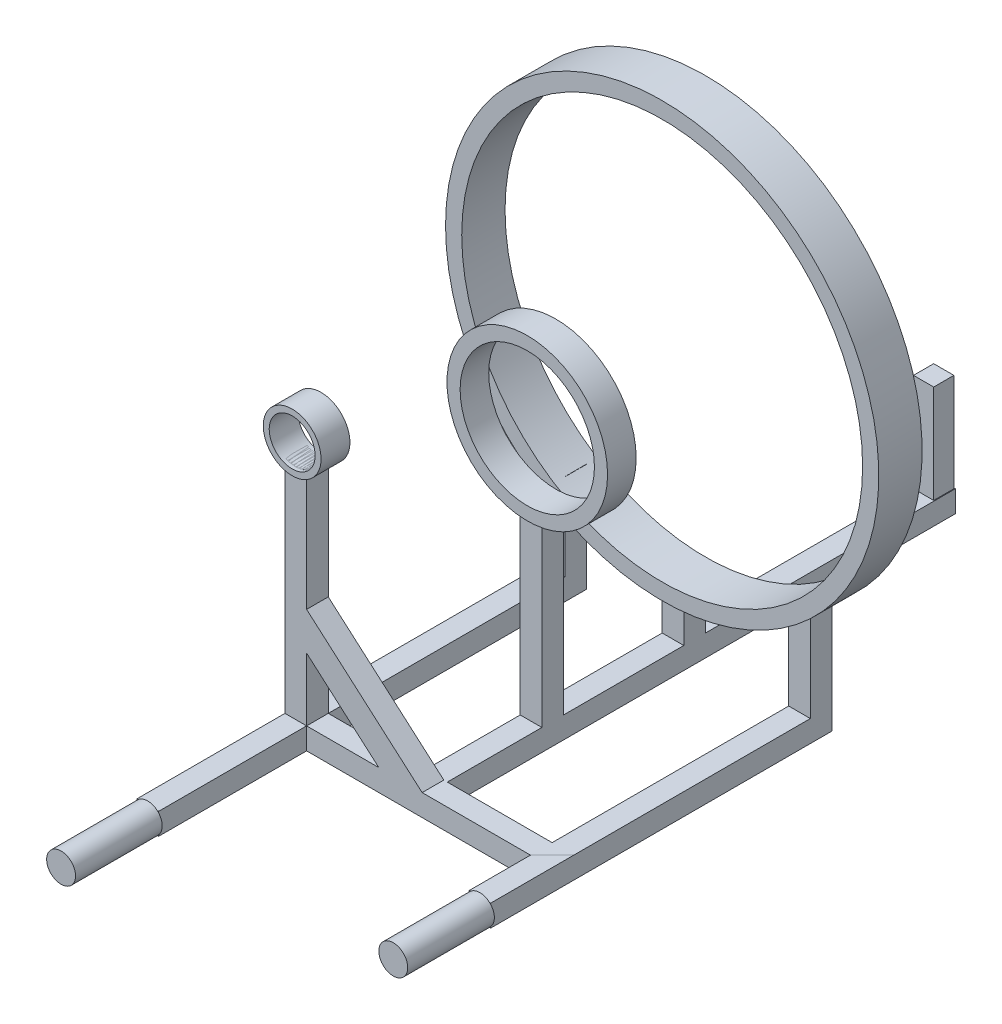
SolidWorks part; units mm, degrees
other "Markup1"
sketch "Sketch15" plane through (18.05, 14, 0) normal (0.0458, 0.1049, 0.9934) x (0.9989, -0.0157, -0.0444)
ref_plane "Front Plane" through (0, 0, 0) normal (0, 0, 1) x (1, 0, 0)
ref_plane "Top Plane" through (0, 0, 0) normal (0, 1, 0) x (1, 0, 0)
ref_plane "Right Plane" through (0, 0, 0) normal (1, 0, 0) x (0, 0, -1)
sketch "Sketch3" plane through (0, 0, 0) normal (0, 0, 1) x (1, 0, 0)
  line L1 (-0.7503, 0.75) -> (0.7497, 0.75)
  line L2 (-0.7503, 0.75) -> (-0.7503, -0.75)
  line L3 (-0.7503, -0.75) -> (0.7497, -0.75)
  line L4 (0.7497, 0.75) -> (0.7497, -0.75)
  line L5 (-0.7503, 0.75) -> (0.7497, -0.75) construction
  line L6 (-0.7503, -0.75) -> (0.7497, 0.75) construction
  dimension "D1" = 1.5
  dimension "D2" = 1.5
sketch "Sketch4" plane through (0, 0, 0) normal (0, 1, 0) x (1, 0, 0)
  line L0 (0, 0) -> (0, 11)
  line L1 (0, 11) -> (17, 11)
  line L2 (17, 11) -> (17, 6)
  dimension "D1" = 17
  dimension "D2" = 11
  dimension "D3" = 5
sweep "Sweep3" add profiles "Sketch3" path "Sketch4"
sketch "Sketch7" plane through (0, 0, 0) normal (0, 1, 0) x (1, 0, 0)
  line L0 (-0.7503, 0) -> (-0.7503, 11.7503) construction
  line L2 (-0.7297, 11.7497) -> (0.7497, 11.7497)
  line L3 (-0.7297, 11.7497) -> (-0.7297, 10.2503)
  line L4 (-0.7297, 10.2503) -> (0.7497, 10.2503)
  line L5 (0.7497, 11.7497) -> (0.7497, 10.2503)
  line L6 (-0.7297, 11.7497) -> (0.7497, 10.2503) construction
  line L7 (-0.7297, 10.2503) -> (0.7497, 11.7497) construction
  circle A0 centre (0.01, 11) radius 0.5 construction
  dimension "D1" = 1
  dimension "D2" = 0.7603
  dimension "D5" = 11
extrude "Boss-Extrude1" add sketch "Sketch7" along normal blind 19
ref_plane "Plane8" through (0, 0, -11) normal (0, 0, 1) x (1, 0, 0)
sketch "Sketch12" plane through (0, 0, -11) normal (0, 0, 1) x (1, 0, 0)
  circle A1 centre (0, 17.5) radius 2
  dimension "D1" = 0
  dimension "D2" = 4
  dimension "D3" = 17.5
extrude "Boss-Extrude4" add sketch "Sketch12" along normal mid plane 2 separate body
ref_plane "Plane9" through (9.09, 0, 0) normal (1, 0, 0) x (0, 0, -1)
sketch "Sketch16" plane through (0, 0, -12) normal (0, 0, -1) x (-1, 0, 0)
  circle A0 centre (0, 17.5) radius 1.59
extrude "Cut-Extrude1" cut sketch "Sketch16" against normal blind 10
sketch "Sketch17" plane through (0, 0, 0) normal (0, 0, 1) x (1, 0, 0)
  circle A0 centre (0, 0) radius 1
  dimension "D1" = 2
extrude "Boss-Extrude5" add sketch "Sketch17" along normal blind 6
sketch "Sketch18" plane through (0, 0, -6) normal (0, 0, 1) x (1, 0, 0)
  line L0 (17.7503, 0.75) -> (17.7503, -0.75) construction
  line L1 (16.2503, 0.75) -> (17.7503, 0.75) construction
  circle A0 centre (17.0006, 0) radius 1
  dimension "D1" = 2
  dimension "D2" = 0.7497
  dimension "D3" = 0.75
extrude "Boss-Extrude6" add sketch "Sketch18" along normal blind 6
ref_plane "Plane10" through (0, 0, -11.75) normal (0, 0, 1) x (1, 0, 0)
sketch "Sketch19" plane through (0, 0, -11.75) normal (0, 0, 1) x (1, 0, 0)
  line L0 (0.7497, -0.75) -> (16.2503, -0.75) construction
  line L1 (7.49, 0.75) -> (8.99, 0.75)
  line L2 (7.49, 0.75) -> (7.49, -0.75)
  line L3 (7.49, -0.75) -> (8.99, -0.75)
  line L4 (8.99, 0.75) -> (8.99, -0.75)
  line L5 (7.49, 0.75) -> (8.99, -0.75) construction
  line L6 (7.49, -0.75) -> (8.99, 0.75) construction
  point P0 (8.24, 0)
  dimension "D1" = 1.5
  dimension "D2" = 1.5
  dimension "D3" = 8.24
extrude "Boss-Extrude7" add sketch "Sketch19" against normal blind 8.05 separate body
sketch "Sketch21" plane through (0, 0.75, 0) normal (0, 1, 0) x (1, 0, 0)
  line L0 (8.99, 19.8) -> (8.99, 11.75) construction
  line L1 (7.49, 19.8) -> (8.99, 19.8)
  line L2 (7.49, 19.8) -> (7.49, 18.3)
  line L3 (7.49, 18.3) -> (8.99, 18.3)
  line L4 (8.99, 19.8) -> (8.99, 18.3)
  dimension "D2" = 1.5
extrude "Boss-Extrude8" add sketch "Sketch21" along normal blind 17.68
ref_plane "Plane11" through (0, 0, -19.05) normal (0, 0, 1) x (1, 0, 0)
sketch "Sketch22" plane through (0, 0, -19.05) normal (0, 0, 1) x (1, 0, 0)
  line L0 (7.49, 0.75) -> (8.99, 0.75) construction
  circle A0 centre (8.2196, 18.43) radius 5.56
  point P4 (8.24, 0.75)
  dimension "D1" = 11.12
  dimension "D2" = 17.68
extrude "Boss-Extrude9" add sketch "Sketch22" along normal mid plane 1.98
sketch "Sketch23" plane through (0, 0, -20.04) normal (0, 0, -1) x (-1, 0, 0)
  circle A0 centre (-8.2196, 18.43) radius 4.65
extrude "Cut-Extrude2" cut sketch "Sketch23" against normal blind 5
sketch "Sketch24" plane through (0, 0, -19.8) normal (0, 0, -1) x (-1, 0, 0)
  line L0 (-7.49, 0.75) -> (-8.99, 0.75) construction
  line L1 (-8.99, -0.75) -> (-7.49, -0.75)
  line L2 (-8.99, -0.75) -> (-8.99, 0.75)
  line L3 (-8.99, 0.75) -> (-7.49, 0.75)
  line L4 (-7.49, -0.75) -> (-7.49, 0.75)
  line L5 (-7.49, 0.75) -> (-8.99, 0.75) construction
extrude "Boss-Extrude10" add sketch "Sketch24" along normal blind 9.83
sketch "Sketch25" plane through (0, 0.75, 0) normal (0, 1, 0) x (1, 0, 0)
  line L0 (8.99, 29.63) -> (8.99, 19.8) construction
  line L1 (7.49, 29.63) -> (8.99, 29.63)
  line L2 (7.49, 29.63) -> (7.49, 28.13)
  line L3 (7.49, 28.13) -> (8.99, 28.13)
  line L4 (8.99, 29.63) -> (8.99, 28.13)
  dimension "D1" = 1.5
extrude "Boss-Extrude11" add sketch "Sketch25" along normal blind 3
ref_plane "Plane12" through (0, 0, -28.88) normal (0, 0, -1) x (-1, 0, 0)
sketch "Sketch27" plane through (0, 0, -28.88) normal (0, 0, -1) x (-1, 0, 0)
  line L0 (-7.49, 0.75) -> (-8.99, 0.75) construction
  circle A0 centre (-8.24, 18.43) radius 15
  dimension "D1" = 30
  dimension "D2" = 17.68
extrude "Boss-Extrude12" add sketch "Sketch27" along normal mid plane 3
sketch "Sketch28" plane through (0, 0, -30.38) normal (0, 0, -1) x (-1, 0, 0)
  circle A0 centre (-8.24, 18.43) radius 13.88
extrude "Cut-Extrude3" cut sketch "Sketch28" against normal blind 3
sketch "Sketch30" plane through (0, 0, -10) normal (0, 0, 1) x (1, 0, 0)
  circle A0 centre (0, 17.5) radius 1.59
extrude "Cut-Extrude5" cut sketch "Sketch30" against normal blind 3
sketch "Sketch31" plane through (0, 0, -29.63) normal (0, 0, -1) x (-1, 0, 0)
  line L0 (-7.49, 0.75) -> (-8.99, 0.75) construction
  line L1 (-8.99, -0.75) -> (-7.49, -0.75)
  line L2 (-8.99, -0.75) -> (-8.99, 0.75)
  line L3 (-8.99, 0.75) -> (-7.49, 0.75)
  line L4 (-7.49, -0.75) -> (-7.49, 0.75)
  line L5 (-7.49, 0.75) -> (-8.99, 0.75) construction
extrude "Boss-Extrude13" add sketch "Sketch31" along normal blind 17.3
sketch "Sketch32" plane through (0, 0.75, 0) normal (0, 1, 0) x (1, 0, 0)
  line L5 (7.49, 46.93) -> (7.49, 29.63) construction
  line L6 (7.54, 46.88) -> (8.94, 46.88)
  line L7 (7.54, 46.88) -> (7.54, 45.48)
  line L8 (7.54, 45.48) -> (8.94, 45.48)
  line L9 (8.94, 46.88) -> (8.94, 45.48)
  line L10 (7.54, 46.88) -> (8.94, 45.48) construction
  line L11 (7.54, 45.48) -> (8.94, 46.88) construction
  line L12 (7.49, 46.93) -> (8.99, 46.93) construction
  point P0 (8.24, 46.18)
  dimension "D1" = 1.4
  dimension "D2" = 1.4
  dimension "D3" = 0.75
  dimension "D4" = 0.75
extrude "Boss-Extrude14" add sketch "Sketch32" along normal blind 6.8
sketch "Sketch33" plane through (0, 0, -11.7503) normal (0, 0, -1) x (-1, 0, 0)
  line L0 (0.7503, -0.75) -> (-17.7503, -0.75) construction
  line L1 (-17.7503, 0.75) -> (-16.2503, 0.75)
  line L2 (-17.7503, 0.75) -> (-17.7503, -0.75)
  line L3 (-17.7503, -0.75) -> (-16.2503, -0.75)
  line L4 (-16.2503, 0.75) -> (-16.2503, -0.75)
  dimension "D1" = 1.5
extrude "Boss-Extrude15" add sketch "Sketch33" along normal blind 17.88
sketch "Sketch34" plane through (0, 0.75, 0) normal (0, 1, 0) x (1, 0, 0)
  line L0 (17.7503, 29.6303) -> (17.7503, 11.7503) construction
  line L1 (16.2503, 29.6303) -> (17.7503, 29.6303)
  line L2 (16.2503, 29.6303) -> (16.2503, 28.1303)
  line L3 (16.2503, 28.1303) -> (17.7503, 28.1303)
  line L4 (17.7503, 29.6303) -> (17.7503, 28.1303)
  dimension "D1" = 1.5
extrude "Boss-Extrude16" add sketch "Sketch34" along normal blind 6
ref_plane "Plane13" through (8.5003, 0, 0) normal (-1, 0, 0) x (0, 0, 1)
mirror "Mirror1" about plane through (8.5003, 0, 0) normal (-1, 0, 0) of "Boss-Extrude16", "Boss-Extrude15"
sketch "Sketch36" plane through (0, 0.75, 0) normal (0, 1, 0) x (1, 0, 0)
  line L0 (0.7503, 11.7503) -> (7.49, 11.7503) construction
  line L1 (5.7497, 11.7503) -> (8.7497, 11.7503)
  line L2 (5.7497, 11.7503) -> (5.7497, 10.2503)
  line L3 (5.7497, 10.2503) -> (8.7497, 10.2503)
  line L4 (8.7497, 11.7503) -> (8.7497, 10.2503)
  line L5 (0.7497, 10.2503) -> (16.2503, 10.2503) construction
  line L6 (0.7497, 10.2503) -> (0.7497, 11.7497) construction
  point P10 (5.7497, 11.0003)
  dimension "D1" = 3
  dimension "D2" = 5
sketch "Sketch37" plane through (0.7497, 0, 0) normal (1, 0, 0) x (0, 0, -1)
  line L0 (10.2503, 16.0978) -> (10.2503, 0.75) construction
  line L1 (10.2503, 5.75) -> (11.7497, 5.75)
  line L2 (10.2503, 5.75) -> (10.2503, 8.75)
  line L3 (10.2503, 8.75) -> (11.7497, 8.75)
  line L4 (11.7497, 5.75) -> (11.7497, 8.75)
  line L5 (11.7497, 16.0978) -> (11.7497, 0.75) construction
  line L6 (10.2503, 0.75) -> (11.7497, 0.75) construction
  point P10 (11, 5.75)
  dimension "D1" = 3
  dimension "D2" = 5
ref_plane "Plane14" through (0, 0, -11.0003) normal (0, 0, 1) x (1, 0, 0)
sketch "Sketch39" plane through (0, 0, -11.0003) normal (0, 0, 1) x (1, 0, 0)
  line L0 (8.24, 0.75) -> (-0.3118, 8.2171)
  line L3 (7.49, 0.75) -> (8.99, 0.75) construction
sweep "Sweep4" add profiles "Sketch36" path "Sketch39"
sketch "Sketch40" plane through (0, 8.2171, 0) normal (0, 1, 0) x (1, 0, 0)
  line L1 (-2.8021, 11.7503) -> (-0.7297, 11.7503)
  line L2 (-2.8021, 11.7503) -> (-2.8021, 10.2503)
  line L3 (-2.8021, 10.2503) -> (-0.7297, 10.2503)
  line L4 (-0.7297, 11.7503) -> (-0.7297, 10.2503)
extrude "Cut-Extrude6" cut sketch "Sketch40" against normal blind 17.13
